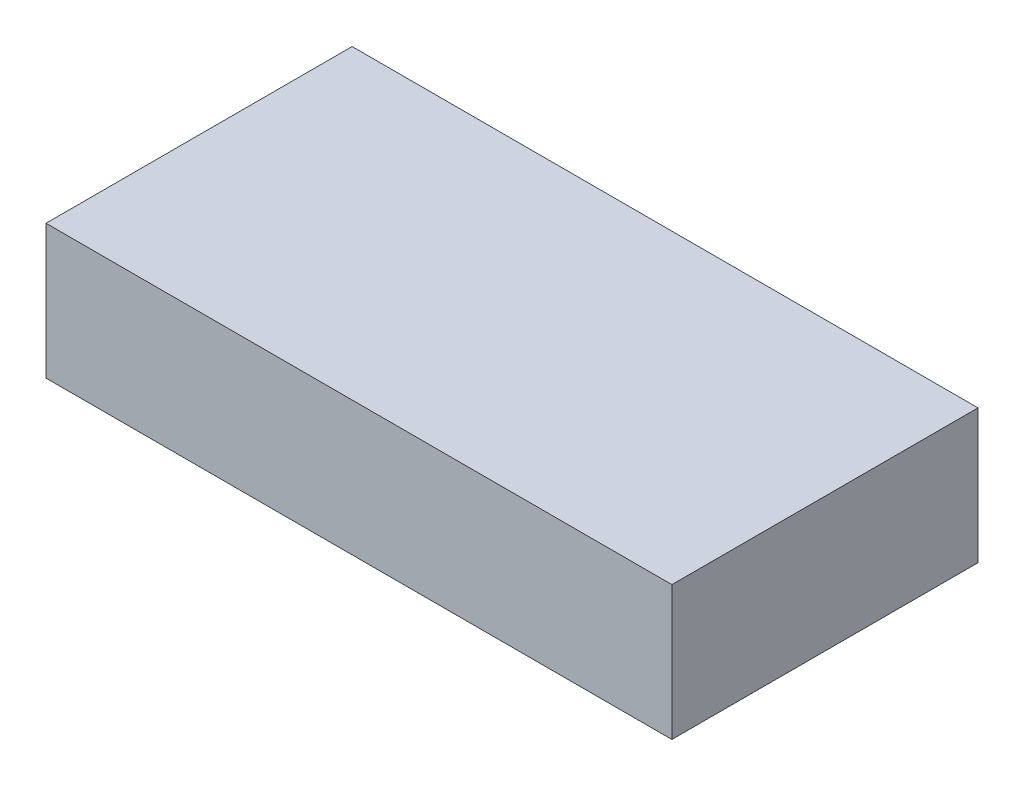
SolidWorks part; units mm, degrees
ref_plane "Front Plane" through (0, 0, 0) normal (0, 0, 1) x (1, 0, 0)
ref_plane "Top Plane" through (0, 0, 0) normal (0, 1, 0) x (1, 0, 0)
ref_plane "Right Plane" through (0, 0, 0) normal (1, 0, 0) x (0, 0, -1)
sketch "Sketch1" plane through (0, 0, 0) normal (0, 1, 0) x (1, 0, 0)
  line L1 (0, 0) -> (70, 0)
  line L2 (0, 0) -> (0, 34.2368)
  line L3 (0, 34.2368) -> (70, 34.2368)
  line L4 (70, 0) -> (70, 34.2368)
  dimension "D1" = 70
sketch "Sketch2" plane through (0, 0, 0) normal (0, 1, 0) x (1, 0, 0)
  line L0 (0, 0) -> (70, 0)
  line L1 (0, 0) -> (0, 34.2368)
  line L2 (0, 34.2368) -> (70, 34.2368)
  line L3 (70, 0) -> (70, 34.2368)
extrude "Boss-Extrude1" add sketch "Sketch2" along normal blind 15
